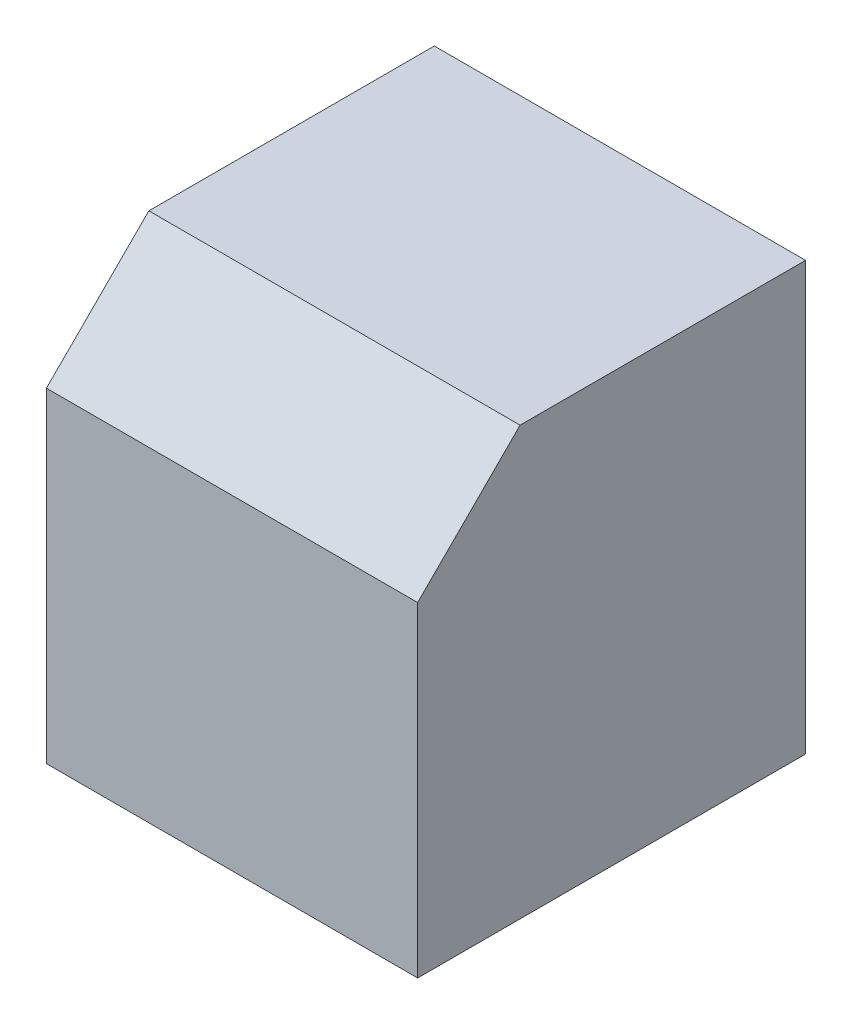
SolidWorks part; units mm, degrees
ref_plane "Front Plane" through (0, 0, 0) normal (0, 0, 1) x (1, 0, 0)
ref_plane "Top Plane" through (0, 0, 0) normal (0, 1, 0) x (1, 0, 0)
ref_plane "Right Plane" through (0, 0, 0) normal (1, 0, 0) x (0, 0, -1)
sketch "Sketch1" plane through (0, 0, 0) normal (0, 0, 1) x (1, 0, 0)
  line L1 (0, 0) -> (29, 0)
  line L2 (0, 0) -> (0, 33.4)
  line L3 (0, 33.4) -> (29, 33.4)
  line L4 (29, 0) -> (29, 33.4)
  dimension "D1" = 29
  dimension "D2" = 33.4
extrude "Boss-Extrude2" add sketch "Sketch1" along normal blind 30.3 contours L3 L4 L1 L2
sketch "Sketch2" plane through (0, 0, 0) normal (-1, 0, 0) x (0, 0, 1)
  line L0 (22.3, 33.4) -> (30.3, 25.4)
  line L1 (30.3, 33.4) -> (0, 33.4) construction
  line L2 (30.3, 0) -> (30.3, 33.4) construction
  line L3 (30.3, 25.4) -> (30.3, 33.4)
  line L4 (30.3, 33.4) -> (22.3, 33.4)
  dimension "D1" = 8
extrude "Cut-Extrude1" cut sketch "Sketch2" against normal through all
